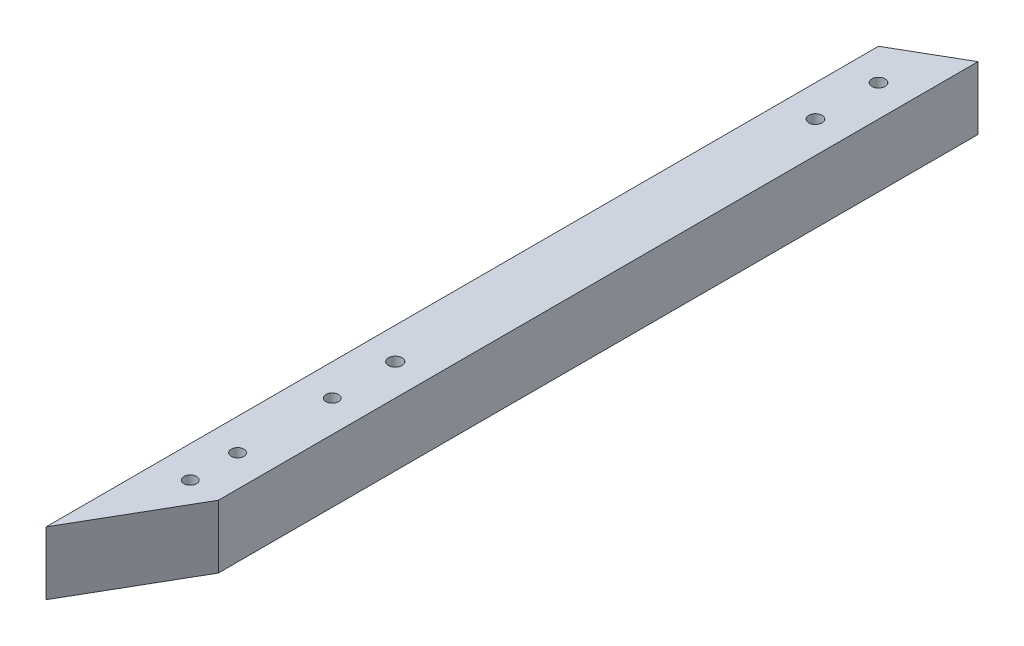
SolidWorks part; units mm, degrees
ref_plane "前视基准面" through (0, 0, 0) normal (0, 0, 1) x (1, 0, 0)
ref_plane "上视基准面" through (0, 0, 0) normal (0, 1, 0) x (1, 0, 0)
ref_plane "右视基准面" through (0, 0, 0) normal (1, 0, 0) x (0, 0, -1)
other "Configuration Table"
sketch "草图1" plane through (0, 0, 0) normal (0, 0, 1) x (1, 0, 0)
  line L1 (0, 0) -> (20, 0)
  line L2 (0, 0) -> (0, 20)
  line L3 (0, 20) -> (20, 20)
  line L4 (20, 0) -> (20, 20)
  dimension "D1" = 20
extrude "凸台-拉伸1" add sketch "草图1" along normal blind 275.47
sketch "草图2" plane through (0, 20, 0) normal (0, 1, 0) x (1, 0, 0)
  line L0 (0, -275.47) -> (20, -240.829)
  line L1 (20, -275.47) -> (20, 0) construction
  line L2 (20, -240.829) -> (20, -275.47)
  line L3 (20, -275.47) -> (0, -275.47)
  line L4 (20, 0) -> (0, -11.547)
  line L5 (0, -275.47) -> (0, 0) construction
  line L6 (0, -11.547) -> (0, 0)
  line L7 (0, 0) -> (20, 0)
  line L8 (20, -275.47) -> (20, 0) construction
  dimension "D1" = 60
  dimension "D2" = 60
extrude "切除-拉伸1" cut sketch "草图2" against normal blind 263.92
sketch "草图3" plane through (0, 0, 0) normal (0, -1, 0) x (1, 0, 0)
  line L0 (10, 258.1495) -> (10, 5.7735) construction
  line L1 (20, 240.829) -> (0, 275.47) construction
  line L2 (0, 11.547) -> (20, 0) construction
  circle A0 centre (10, 239.74) radius 2
  circle A1 centre (10, 224.74) radius 2
  circle A2 centre (10, 194.74) radius 2
  circle A3 centre (10, 174.74) radius 2.15
  dimension "D2" = 15
  dimension "D4" = 4
  dimension "D5" = 4.3
  dimension "D6" = 20
  dimension "D1" = 35.73
  dimension "D3" = 30
extrude "切除-拉伸2" cut sketch "草图3" against normal through all both
sketch "草图4" plane through (0, 0, 0) normal (0, -1, 0) x (1, 0, 0)
  line L0 (0, 11.547) -> (35.5625, 11.547) construction
  line L1 (10, 5.7735) -> (10, 134.4239) construction
  line L2 (0, 11.547) -> (20, 0) construction
  circle A0 centre (10, 21.547) radius 2.1
  circle A1 centre (10, 41.547) radius 2.1
  circle A2 centre (10, 174.74) radius 2.15 construction
  dimension "D1" = 4.2
  dimension "D2" = 10
  dimension "D4" = 4.2
  dimension "D5" = 20
  dimension "D6" = 133.193
  dimension "D3" = 11.547
extrude "切除-拉伸3" cut sketch "草图4" against normal blind 60
